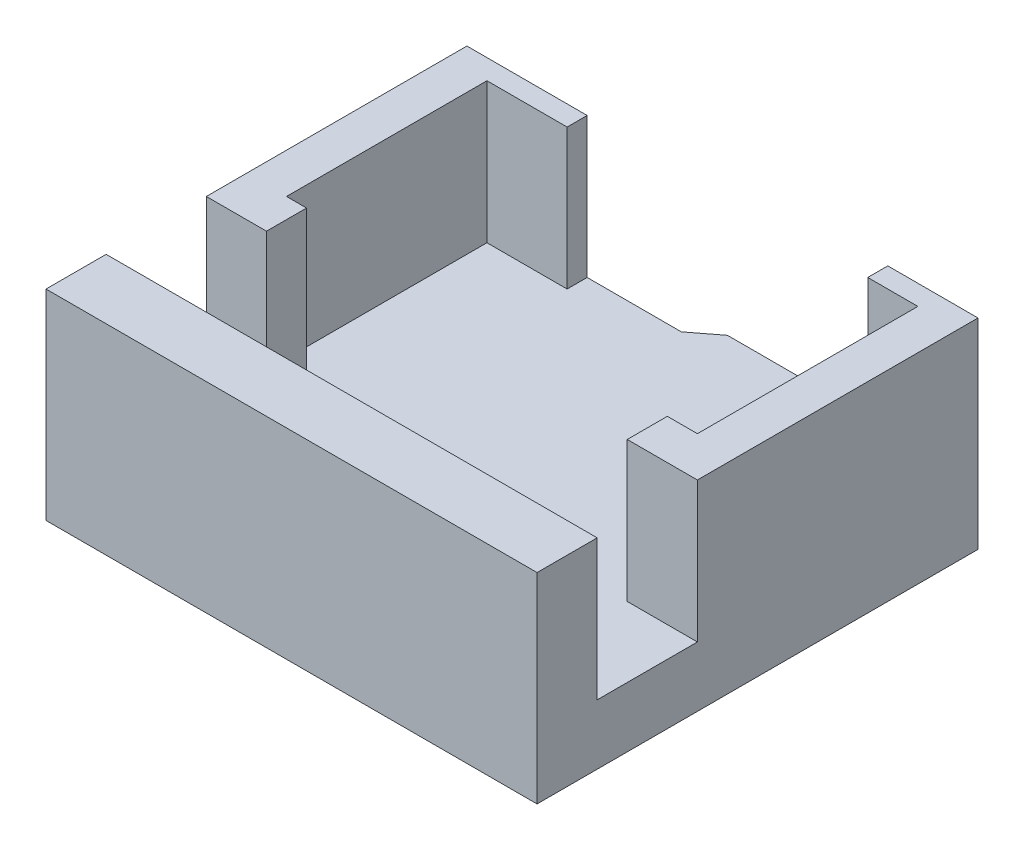
SolidWorks part; units mm, degrees
ref_plane "Front Plane" through (0, 0, 0) normal (0, 0, 1) x (1, 0, 0)
ref_plane "Top Plane" through (0, 0, 0) normal (0, 1, 0) x (1, 0, 0)
ref_plane "Right Plane" through (0, 0, 0) normal (1, 0, 0) x (0, 0, -1)
sketch "Sketch1" plane through (0, 0, 0) normal (0, 1, 0) x (1, 0, 0)
  line L0 (-38.972, -19.2346) -> (-37.972, -19.2346)
  line L1 (-18.972, -19.2346) -> (-18.972, -8.2346)
  line L2 (-38.972, -19.2346) -> (-38.972, -9.2346)
  line L6 (-38.972, -9.2346) -> (-34.972, -9.2346)
  line L7 (-34.972, -9.2346) -> (-34.972, -8.2346)
  line L8 (-34.972, -8.2346) -> (-40.972, -8.2346)
  line L9 (-40.972, -8.2346) -> (-40.972, -21.2346)
  line L10 (-40.972, -21.2346) -> (-37.972, -21.2346)
  line L11 (-37.972, -21.2346) -> (-37.972, -19.2346)
  line L12 (-18.972, -8.2346) -> (-20.972, -8.2346)
  line L13 (-20.972, -8.2346) -> (-20.972, -7.2346)
  line L14 (-20.972, -7.2346) -> (-16.972, -7.2346)
  line L15 (-16.972, -7.2346) -> (-16.972, -21.2346)
  line L16 (-19.972, -19.2346) -> (-18.972, -19.2346)
  line L17 (-16.972, -21.2346) -> (-19.972, -21.2346)
  line L19 (-19.972, -19.2346) -> (-19.972, -21.2346)
extrude "Boss-Extrude1" add sketch "Sketch1" along normal blind 7
sketch "Sketch2" plane through (0, 0, 0) normal (0, -1, 0) x (1, 0, 0)
  line L0 (-40.972, 21.2346) -> (-16.972, 21.2346)
  line L1 (-16.972, 21.2346) -> (-16.972, 7.2346)
  line L2 (-16.972, 21.2346) -> (-16.972, 7.2346) construction
  line L3 (-16.972, 7.2346) -> (-20.972, 7.2346) construction
  line L4 (-16.972, 7.2346) -> (-28.972, 7.2346)
  line L5 (-28.972, 7.2346) -> (-30.2736, 8.2346)
  line L6 (-30.2736, 8.2346) -> (-40.972, 8.2346)
  line L7 (-40.972, 8.2346) -> (-40.972, 21.2346)
extrude "Boss-Extrude2" add sketch "Sketch2" along normal blind 2
sketch "Sketch4" plane through (-16.972, 0, 0) normal (1, 0, 0) x (0, 0, -1)
  line L1 (-7.2346, -2) -> (-21.2346, -2)
  line L2 (-7.2346, -2) -> (-7.2346, 7)
  line L3 (-7.2346, 7) -> (-21.2346, 7)
  line L4 (-21.2346, -2) -> (-21.2346, 7)
extrude "Boss-Extrude3" add sketch "Sketch4" along normal blind 0.5
sketch "Sketch5" plane through (-18.972, 0, 0) normal (-1, 0, 0) x (0, 0, 1)
  line L1 (8.2346, 7) -> (19.2346, 7)
  line L2 (8.2346, 7) -> (8.2346, 0)
  line L3 (8.2346, 0) -> (19.2346, 0)
  line L4 (19.2346, 7) -> (19.2346, 0)
extrude "Cut-Extrude1" cut sketch "Sketch5" against normal blind 0.5
sketch "Sketch6" plane through (0, 0, 21.2346) normal (0, 0, 1) x (1, 0, 0)
  line L0 (-16.472, 7) -> (-16.472, -2) construction
  line L1 (-40.972, -2) -> (-16.472, -2)
  line L2 (-40.972, -2) -> (-40.972, 0)
  line L3 (-40.972, 0) -> (-16.472, 0)
  line L4 (-16.472, -2) -> (-16.472, 0)
extrude "Boss-Extrude4" add sketch "Sketch6" along normal blind 8
sketch "Sketch7" plane through (0, 0, 0) normal (0, 1, 0) x (1, 0, 0)
  line L0 (-16.472, -29.2346) -> (-16.472, -21.2346) construction
  line L1 (-40.972, -29.2346) -> (-16.472, -29.2346)
  line L2 (-40.972, -29.2346) -> (-40.972, -26.2346)
  line L3 (-40.972, -26.2346) -> (-16.472, -26.2346)
  line L4 (-16.472, -29.2346) -> (-16.472, -26.2346)
  dimension "D1" = 3
extrude "Boss-Extrude5" add sketch "Sketch7" along normal up to surface (7 mm away) up to face at (-18.972, 7, 13.9846)
sketch "Sketch8" plane through (0, -2, 0) normal (0, -1, 0) x (1, 0, 0)
  line L6 (-40.972, 29.2346) -> (-40.972, 8.2346)
  line L7 (-40.972, 8.2346) -> (-30.2736, 8.2346)
  line L8 (-30.2736, 8.2346) -> (-28.972, 7.2346)
  line L9 (-28.972, 7.2346) -> (-16.472, 7.2346)
  line L10 (-16.472, 7.2346) -> (-16.472, 29.2346)
  line L11 (-16.472, 29.2346) -> (-40.972, 29.2346)
  line L12 (-40.972, 29.2346) -> (-40.972, 8.2346)
  line L13 (-40.972, 8.2346) -> (-30.2736, 8.2346)
  line L14 (-30.2736, 8.2346) -> (-28.972, 7.2346)
  line L15 (-28.972, 7.2346) -> (-16.472, 7.2346)
  line L16 (-16.472, 7.2346) -> (-16.472, 29.2346)
  line L17 (-16.472, 29.2346) -> (-40.972, 29.2346)
  dimension "D1" = 0
extrude "Boss-Extrude6" add sketch "Sketch8" along normal blind 1
